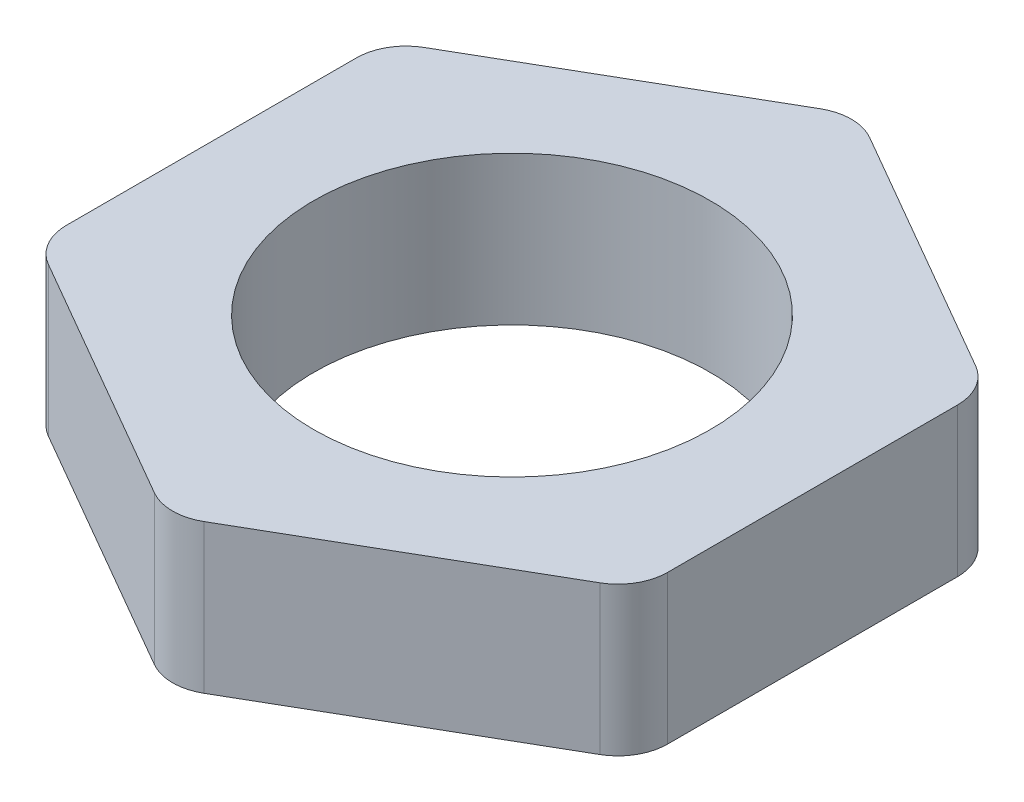
SolidWorks part; units mm, degrees
ref_plane "Front Plane" through (0, 0, 0) normal (0, 0, 1) x (1, 0, 0)
ref_plane "Top Plane" through (0, 0, 0) normal (0, 1, 0) x (1, 0, 0)
ref_plane "Right Plane" through (0, 0, 0) normal (1, 0, 0) x (0, 0, -1)
sketch "Sketch1" plane through (0, 0, 0) normal (0, 1, 0) x (1, 0, 0)
  line L1 (5.5622, 3.7887) -> (0.5, 6.7113)
  line L2 (-0.5, 6.7113) -> (-5.5622, 3.7887)
  line L3 (-6.0622, 2.9226) -> (-6.0622, -2.9226)
  line L4 (-5.5622, -3.7887) -> (-0.5, -6.7113)
  line L5 (0.5, -6.7113) -> (5.5622, -3.7887)
  line L6 (6.0622, -2.9226) -> (6.0622, 2.9226)
  circle A0 centre (0, 0) radius 4
  circle A2 centre (0, 0) radius 6.0622 construction
  circle A3 centre (0, 0) radius 7 construction
  arc A4 (-5.5622, 3.7887) -> (-6.0622, 2.9226) centre (-5.0622, 2.9226) ccw
  arc A5 (-6.0622, -2.9226) -> (-5.5622, -3.7887) centre (-5.0622, -2.9226) ccw
  arc A6 (-0.5, -6.7113) -> (0.5, -6.7113) centre (0, -5.8453) ccw
  arc A7 (5.5622, -3.7887) -> (6.0622, -2.9226) centre (5.0622, -2.9226) ccw
  arc A8 (5.5622, 3.7887) -> (6.0622, 2.9226) centre (5.0622, 2.9226) cw
  arc A9 (0.5, 6.7113) -> (-0.5, 6.7113) centre (0, 5.8453) ccw
  point P23 (0, 7)
  dimension "D1" = 8
  dimension "D2" = 14
  dimension "D3" = 1
extrude "Boss-Extrude1" add sketch "Sketch1" along normal mid plane 3
cosmetic thread "Cosmetic Thread1" parameters "D1"=3, "D2"=9.728
